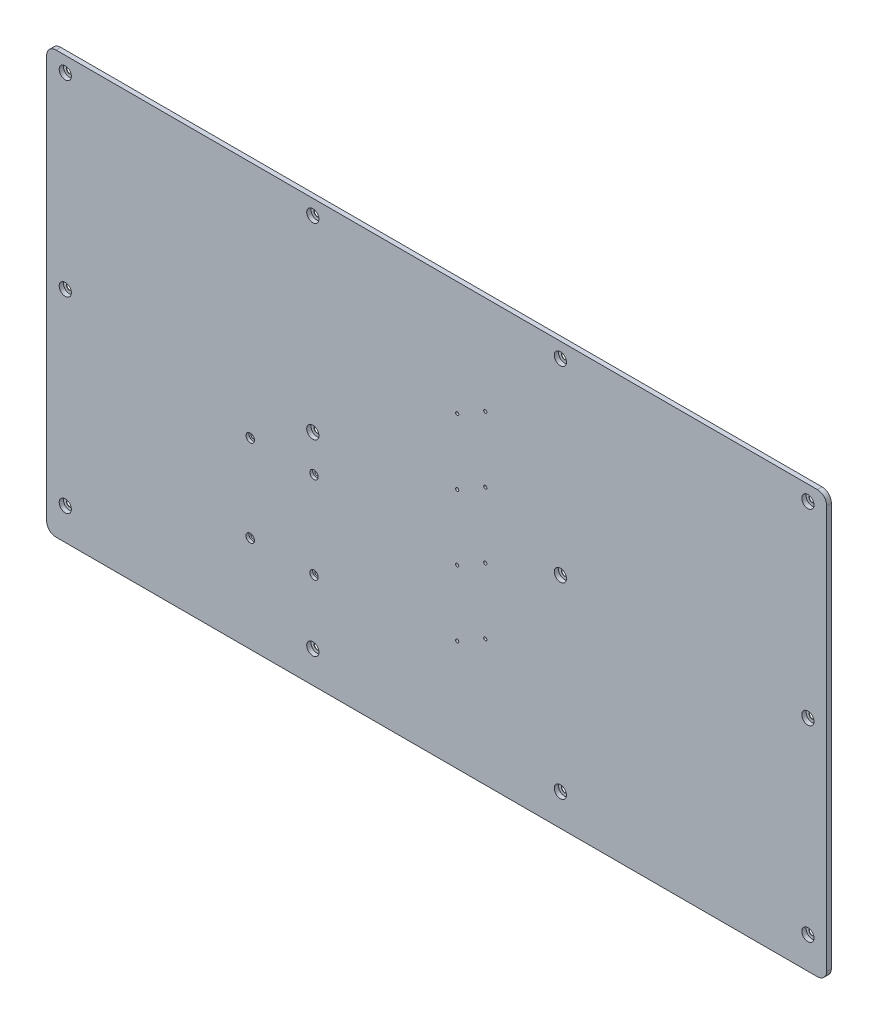
SolidWorks part; units mm, degrees
ref_plane "Plan de face" through (0, 0, 0) normal (0, 0, 1) x (1, 0, 0)
ref_plane "Plan de dessus" through (0, 0, 0) normal (0, 1, 0) x (1, 0, 0)
ref_plane "Plan de droite" through (0, 0, 0) normal (1, 0, 0) x (0, 0, -1)
sketch "Esquisse1" plane through (0, 0, 0) normal (0, 0, 1) x (1, 0, 0)
  line L1 (-406, -225) -> (406, -225)
  line L2 (-416, -215) -> (-416, 215)
  line L3 (-406, 225) -> (406, 225)
  line L4 (416, -215) -> (416, 215)
  line L5 (-416, -225) -> (416, 225) construction
  line L6 (-416, 225) -> (416, -225) construction
  arc A0 (416, 215) -> (406, 225) centre (406, 215) ccw
  arc A1 (406, -225) -> (416, -215) centre (406, -215) ccw
  arc A2 (-406, -225) -> (-416, -215) centre (-406, -215) cw
  arc A3 (-416, 215) -> (-406, 225) centre (-406, 215) cw
  point P0 (0, 0)
  dimension "D3" = 10
  dimension "D1" = 832
  dimension "D2" = 450
extrude "Boss.-Extru.1" add sketch "Esquisse1" along normal blind 5
hole_wizard "Dégagement M61" positions "Esquisse3" profile "Esquisse2" hole size "M6" standard "JIS" end condition through all
sketch "Esquisse3" plane through (0, 0, 0) normal (0, 0, -1) x (-1, 0, 0)
  point P0 (-395.9198, 208.8724)
sketch "Esquisse2" plane through (395.9198, 208.8724, 0) normal (1, 0, 0) x (0, 1, 0)
  line L0 (0, 0) -> (0, 5)
  line L1 (0, 5) -> (3.3, 5)
  line L2 (3.3, 5) -> (3.3, 0)
  line L5 (3.3, 0) -> (0, 0)
  line L11 (0, -6.35) -> (0, 107.95) construction
  dimension "Diamètre du perçage jusqu'au prochain" = 6.6
  dimension "Profondeur du perçage jusqu'au prochain" = 5
hole_wizard "Chambrage pour vis à tête ronde bombée M61" positions "Esquisse5" profile "Esquisse4" counterbore size "M6" standard "Ansi Metric" end condition through all
sketch "Esquisse5" plane through (0, 0, 5) normal (0, 0, 1) x (1, 0, 0)
  point P0 (395.9198, 208.8724)
sketch "Esquisse4" plane through (395.9198, 208.8724, 5) normal (1, 0, 0) x (0, -1, 0)
  line L0 (0, 0) -> (0, 5)
  line L1 (0, 5) -> (3.3, 5)
  line L2 (3.3, 4.625) -> (3.3, 5)
  line L3 (3.3, 4.625) -> (3.325, 4.6)
  line L4 (3.325, 4.6) -> (6.5, 4.6)
  line L5 (6.5, 4.6) -> (6.5, 0)
  line L7 (0, 0) -> (6.5, 0)
  line L9 (-3.3, 4.625) -> (-3.325, 4.6) construction
  line L11 (0, -6.35) -> (0, 107.95) construction
  dimension "Diamètre du perçage jusqu'au prochain" = 6.6
  dimension "Profondeur du perçage jusqu'au prochain" = 5
  dimension "Diamètre du chambrage" = 13
  dimension "Profondeur du chambrage" = 4.6
  dimension "Diamètre du fraisage milieu" = 6.65
  dimension "Angle du fraisage milieu" = 90
pattern_linear "Répétition linéaire1" count 5 spacing 100 along (0, -1, 0) count 4 spacing 264 along (-1, 0, 0) skipping (1, 0), (1, 1), (1, 2), (1, 3), (3, 0), (3, 1), (3, 2), (3, 3) of "Chambrage pour vis à tête ronde bombée M61"
hole_wizard "Chambrage pour vis à tête ronde bombée M42" positions "Esquisse10" profile "Esquisse9" counterbore size "M4" standard "Ansi Metric" end condition through all
sketch "Esquisse10" plane through (0, 0, 5) normal (0, 0, 1) x (1, 0, 0)
  point P0 (-130.8155, -122.2563)
  point P2 (-130.8155, -29.7118)
sketch "Esquisse9" plane through (-130.8155, -122.2563, 5) normal (1, 0, 0) x (0, -1, 0)
  line L0 (0, 0) -> (0, 5)
  line L1 (0, 5) -> (2.25, 5)
  line L2 (2.25, 3.125) -> (2.25, 5)
  line L3 (2.25, 3.125) -> (2.275, 3.1)
  line L4 (2.275, 3.1) -> (4.5, 3.1)
  line L5 (4.5, 3.1) -> (4.5, 0)
  line L7 (0, 0) -> (4.5, 0)
  line L9 (-2.25, 3.125) -> (-2.275, 3.1) construction
  line L11 (0, -6.35) -> (0, 107.95) construction
  dimension "Diamètre du perçage jusqu'au prochain" = 4.5
  dimension "Profondeur du perçage jusqu'au prochain" = 5
  dimension "Diamètre du chambrage" = 9
  dimension "Profondeur du chambrage" = 3.1
  dimension "Diamètre du fraisage milieu" = 4.55
  dimension "Angle du fraisage milieu" = 90
pattern_linear "Répétition linéaire3" count 2 spacing 68 along (-1, 0, 0) of "Chambrage pour vis à tête ronde bombée M42"
hole_wizard "M3 Clearance Hole1" positions "Sketch2" profile "Sketch1" hole size "M3" standard "ANSI Metric" end condition through all
sketch "Sketch2" plane through (0, 0, 5) normal (0, 0, 1) x (1, 0, 0)
  point P0 (21.8921, -106.9135)
  point P3 (51.8921, -89.9135)
sketch "Sketch1" plane through (21.8921, -106.9135, 5) normal (1, 0, 0) x (0, -1, 0)
  line L0 (0, 0) -> (0, 5)
  line L1 (0, 5) -> (1.7, 5)
  line L2 (1.7, 5) -> (1.7, 0)
  line L5 (1.7, 0) -> (0, 0)
  line L11 (0, -6.35) -> (0, 107.95) construction
  dimension "Thru Hole Dia." = 3.4
  dimension "Thru Hole Depth" = 5
pattern_linear "LPattern1" count 4 spacing 70 along (0, 1, 0) of "M3 Clearance Hole1"
